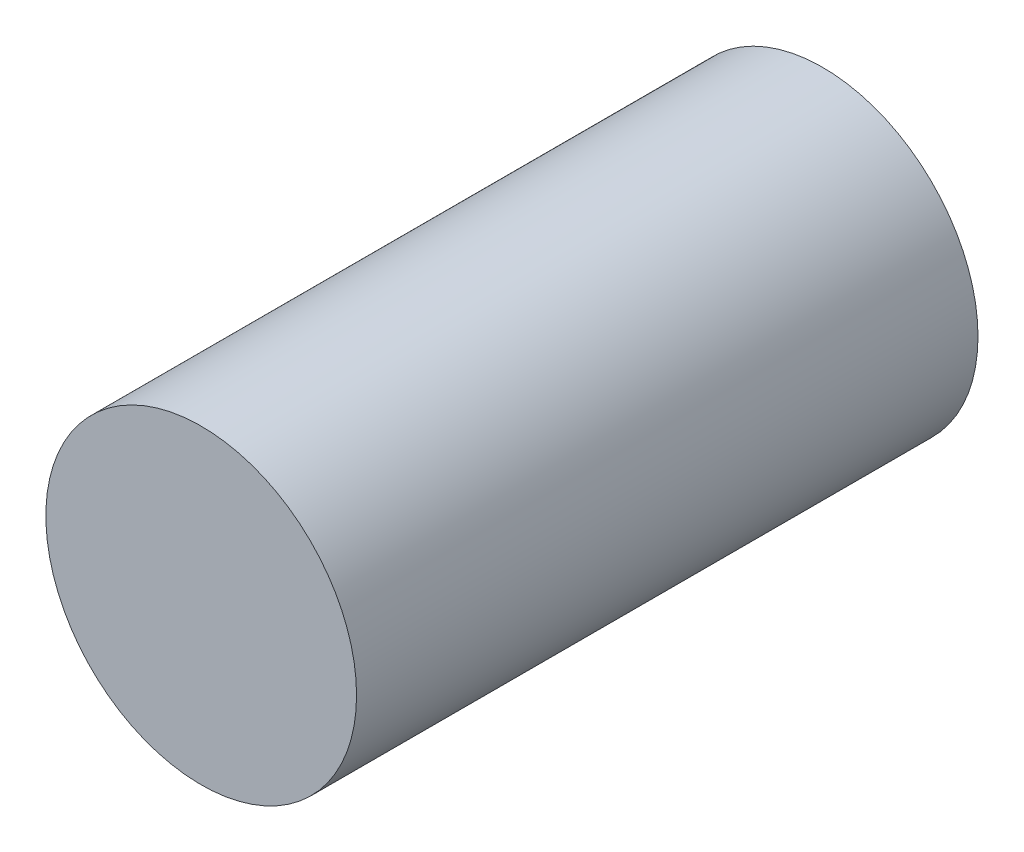
SolidWorks part; units mm, degrees
ref_plane "Front Plane" through (0, 0, 0) normal (0, 0, 1) x (1, 0, 0)
ref_plane "Top Plane" through (0, 0, 0) normal (0, 1, 0) x (1, 0, 0)
ref_plane "Right Plane" through (0, 0, 0) normal (1, 0, 0) x (0, 0, -1)
sketch "Sketch1" plane through (0, 0, 0) normal (0, 0, 1) x (1, 0, 0)
  circle A0 centre (-12.7409, 14.2322) radius 6.35
  dimension "D1" = 12.7
extrude "Boss-Extrude1" add sketch "Sketch1" along normal blind 25.4
